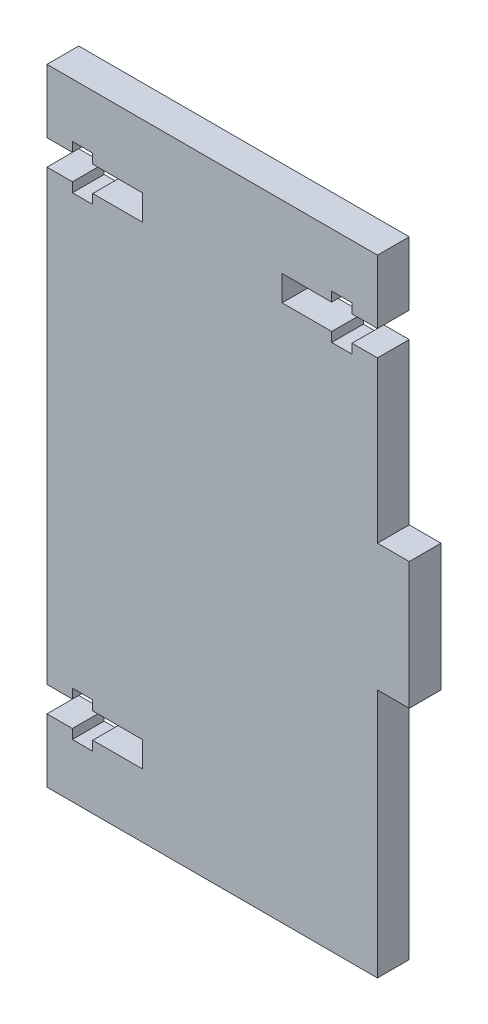
SolidWorks part; units mm, degrees
ref_plane "Front Plane" through (0, 0, 0) normal (0, 0, 1) x (1, 0, 0)
ref_plane "Top Plane" through (0, 0, 0) normal (0, 1, 0) x (1, 0, 0)
ref_plane "Right Plane" through (0, 0, 0) normal (1, 0, 0) x (0, 0, -1)
sketch "Sketch1" plane through (0, 0, 0) normal (0, 0, 1) x (1, 0, 0)
  line L0 (26, 10) -> (31, 10)
  line L1 (-26, 49.25) -> (26, 49.25)
  line L2 (-26, 49.25) -> (-26, -49.25)
  line L3 (-26, -49.25) -> (26, -49.25)
  line L4 (26, 49.25) -> (26, 10)
  line L5 (31, 10) -> (31, -10)
  line L6 (31, -10) -> (26, -10)
  line L7 (26, -10) -> (26, -49.25)
  dimension "D1" = 98.5
  dimension "D2" = 49.25
  dimension "D3" = 52
  dimension "D4" = 26
  dimension "D5" = 10
  dimension "D6" = 10
  dimension "D7" = 5
extrude "Boss-Extrude1" add sketch "Sketch1" along normal blind 5
sketch "Sketch2" plane through (0, 0, 0) normal (0, 0, -1) x (-1, 0, 0)
  line L0 (26, 39.25) -> (22, 39.25)
  line L1 (26, 49.25) -> (26, -49.25) construction
  line L2 (22, 39.25) -> (22, 40.75)
  line L3 (22, 40.75) -> (18.8, 40.75)
  line L4 (18.8, 40.75) -> (18.8, 39.25)
  line L5 (18.8, 39.25) -> (11, 39.25)
  line L6 (11, 39.25) -> (11, 35.25)
  line L7 (11, 35.25) -> (18.8, 35.25)
  line L8 (18.8, 35.25) -> (18.8, 33.75)
  line L9 (18.8, 33.75) -> (22, 33.75)
  line L10 (22, 33.75) -> (22, 35.25)
  line L11 (22, 35.25) -> (26, 35.25)
  line L12 (26, 35.25) -> (26, 39.25)
  line L13 (0, 0) -> (31.9642, 0) construction
  line L14 (0, 0) -> (0, 27.0563) construction
  line L15 (26, -35.25) -> (26, -39.25)
  line L16 (22, -35.25) -> (26, -35.25)
  line L17 (22, -33.75) -> (22, -35.25)
  line L18 (18.8, -33.75) -> (22, -33.75)
  line L19 (18.8, -35.25) -> (18.8, -33.75)
  line L20 (11, -35.25) -> (18.8, -35.25)
  line L21 (11, -39.25) -> (11, -35.25)
  line L22 (18.8, -39.25) -> (11, -39.25)
  line L23 (18.8, -40.75) -> (18.8, -39.25)
  line L24 (22, -40.75) -> (18.8, -40.75)
  line L25 (22, -39.25) -> (22, -40.75)
  line L26 (26, -39.25) -> (22, -39.25)
  line L39 (-26, 35.25) -> (-26, 39.25)
  line L40 (-22, 35.25) -> (-26, 35.25)
  line L41 (-22, 33.75) -> (-22, 35.25)
  line L42 (-18.8, 33.75) -> (-22, 33.75)
  line L43 (-18.8, 35.25) -> (-18.8, 33.75)
  line L44 (-11, 35.25) -> (-18.8, 35.25)
  line L45 (-11, 39.25) -> (-11, 35.25)
  line L46 (-18.8, 39.25) -> (-11, 39.25)
  line L47 (-18.8, 40.75) -> (-18.8, 39.25)
  line L48 (-22, 40.75) -> (-18.8, 40.75)
  line L49 (-22, 39.25) -> (-22, 40.75)
  line L50 (-26, 39.25) -> (-22, 39.25)
  line L51 (-26, 49.25) -> (26, 49.25) construction
  dimension "D1" = 4
  dimension "D2" = 4
  dimension "D3" = 3.2
  dimension "D4" = 1.5
  dimension "D5" = 1.5
  dimension "D6" = 15
  dimension "D7" = 10
extrude "Cut-Extrude1" cut sketch "Sketch2" against normal blind 10
